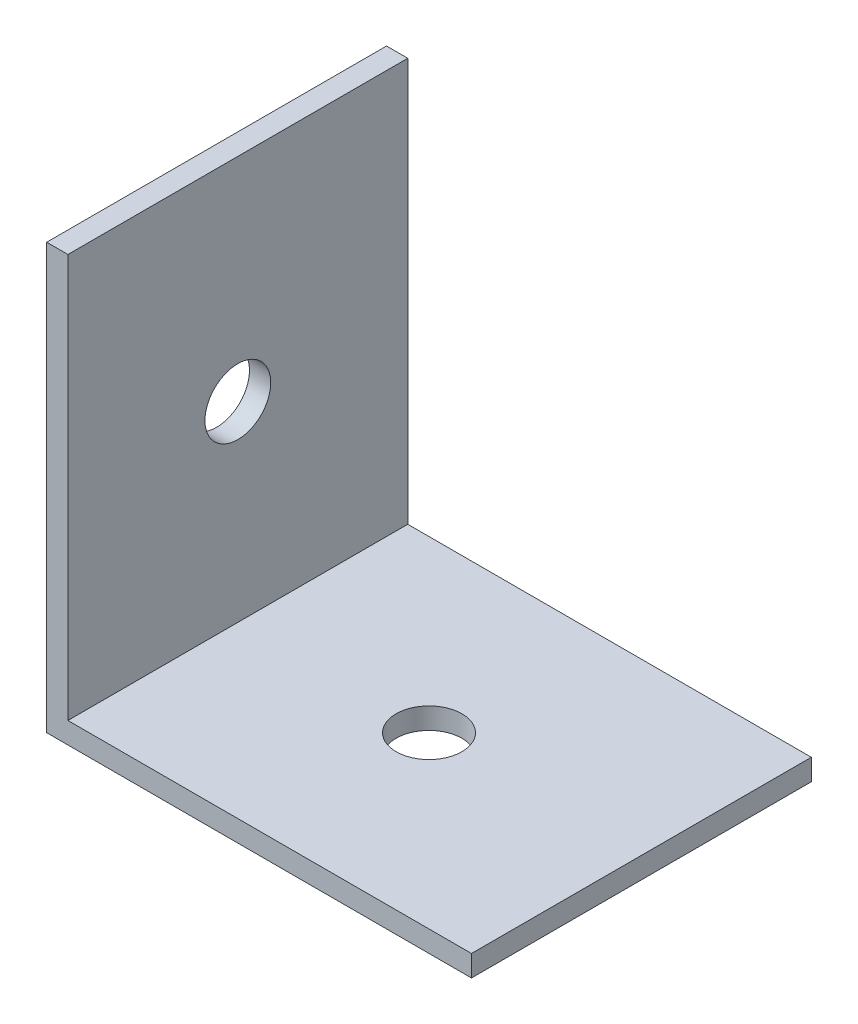
SolidWorks part; units mm, degrees
material "6061 Alloy"
ref_plane "Front" through (0, 0, 0) normal (0, 0, 1) x (1, 0, 0)
ref_plane "Top" through (0, 0, 0) normal (0, 1, 0) x (1, 0, 0)
ref_plane "Right" through (0, 0, 0) normal (1, 0, 0) x (0, 0, -1)
sketch "Sketch1" plane through (0, 0, 0) normal (0, 0, 1) x (1, 0, 0)
  line L0 (0, 0) -> (0, 31.75)
  line L1 (0, 31.75) -> (1.5875, 31.75)
  line L2 (1.5875, 31.75) -> (1.5875, 1.5875)
  line L3 (1.5875, 1.5875) -> (31.75, 1.5875)
  line L4 (31.75, 1.5875) -> (31.75, 0)
  line L5 (0, 0) -> (31.75, 0)
  dimension "D1" = 1.5875
  dimension "D2" = 1.5875
  dimension "D3" = 31.75
  dimension "D4" = 31.75
extrude "Boss-Extrude1" add sketch "Sketch1" along normal blind 25.4
hole_wizard "#10 (0.1935) Diameter Hole1" positions "Sketch2" profile "Sketch3" hole size "#10" standard "ANSI Inch" end condition through all
sketch "Sketch2" plane through (0, 0, 0) normal (0, -1, 0) x (-1, 0, 0)
  line L0 (-31.75, -12.7) -> (0, -12.7) construction
  line L1 (-31.75, -25.4) -> (-31.75, 0) construction
  line L2 (0, -25.4) -> (0, 0) construction
  line L4 (-15.875, -25.4) -> (-15.875, 0) construction
  line L5 (0, -25.4) -> (-31.75, -25.4) construction
  line L6 (0, 0) -> (-31.75, 0) construction
  point P0 (-15.875, -12.7)
  dimension "D1" = 0
  dimension "D2" = 0
sketch "Sketch3" plane through (15.875, 0, 12.7) normal (1, 0, 0) x (0, 0, -1)
  line L0 (0, 0) -> (0, 31.75)
  line L1 (0, 31.75) -> (2.4574, 31.75)
  line L2 (2.4574, 31.75) -> (2.4574, 0)
  line L5 (2.4574, 0) -> (0, 0)
  line L11 (0, -6.35) -> (0, 107.95) construction
  dimension "Thru Hole Dia." = 4.9149
  dimension "Thru Hole Depth" = 31.75
hole_wizard "#10 (0.1935) Diameter Hole2" positions "Sketch4" profile "Sketch5" hole size "#10" standard "ANSI Inch" end condition through all
sketch "Sketch4" plane through (0, 0, 0) normal (-1, 0, 0) x (0, 0, 1)
  line L0 (12.7, 31.75) -> (12.7, 0) construction
  line L1 (25.4, 31.75) -> (0, 31.75) construction
  line L2 (25.4, 0) -> (0, 0) construction
  line L4 (0, 15.875) -> (25.4, 15.875) construction
  line L5 (0, 31.75) -> (0, 0) construction
  line L6 (25.4, 31.75) -> (25.4, 0) construction
  point P0 (12.7, 15.875)
  dimension "D1" = 0
  dimension "D2" = 0
sketch "Sketch5" plane through (0, 15.875, 12.7) normal (0, 1, 0) x (0, 0, 1)
  line L0 (0, 0) -> (0, 31.75)
  line L1 (0, 31.75) -> (2.4574, 31.75)
  line L2 (2.4574, 31.75) -> (2.4574, 0)
  line L5 (2.4574, 0) -> (0, 0)
  line L11 (0, -6.35) -> (0, 107.95) construction
  dimension "Thru Hole Dia." = 4.9149
  dimension "Thru Hole Depth" = 31.75
